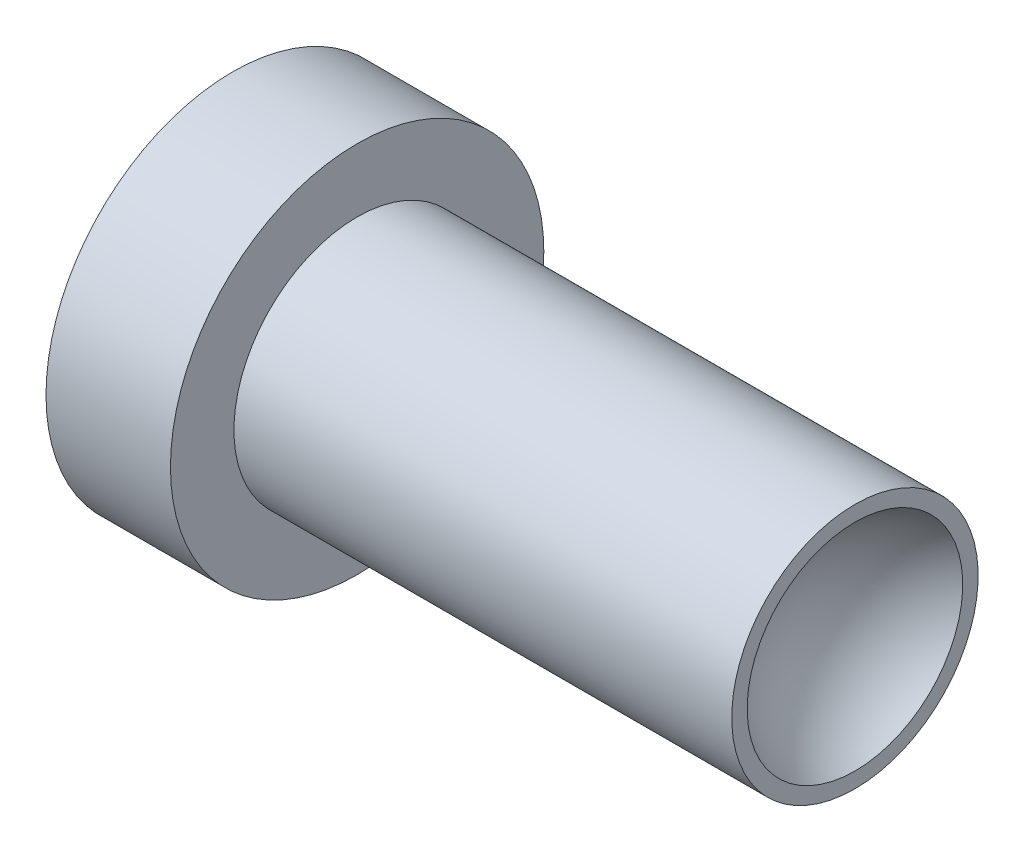
SolidWorks part; units mm, degrees
ref_plane "Front Plane" through (0, 0, 0) normal (0, 0, 1) x (1, 0, 0)
ref_plane "Top Plane" through (0, 0, 0) normal (0, 1, 0) x (1, 0, 0)
ref_plane "Right Plane" through (0, 0, 0) normal (1, 0, 0) x (0, 0, -1)
sketch "Sketch1" plane through (0, 0, 0) normal (0, 0, 1) x (1, 0, 0)
  line L0 (0, 0) -> (0, 19.05)
  line L1 (0, 19.05) -> (12.7, 19.05)
  line L2 (12.7, 19.05) -> (12.7, 12.573)
  line L3 (12.7, 12.573) -> (63.5, 12.573)
  line L4 (63.5, 12.573) -> (63.5, 0)
  line L5 (63.5, 0) -> (0, 0)
  dimension "D1" = 12.7
  dimension "D2" = 50.8
  dimension "D3" = 12.573
  dimension "D4" = 19.05
revolve "Revolve1" add sketch "Sketch1" angle 360 about L5
sketch "Sketch2" plane through (0, 0, 0) normal (0, 0, 1) x (1, 0, 0)
  line L0 (63.5, -12.573) -> (63.5, 12.573) construction
  line L1 (63.5, -10.9985) -> (63.5, 0)
  line L2 (63.5, 0) -> (57.15, 0)
  arc A0 (57.15, 0) -> (63.5, -10.9985) centre (69.85, 0) ccw
  dimension "D2" = 12.7
  dimension "D1" = 6.35
revolve "Cut-Revolve1" cut sketch "Sketch2" angle 360 about L2
